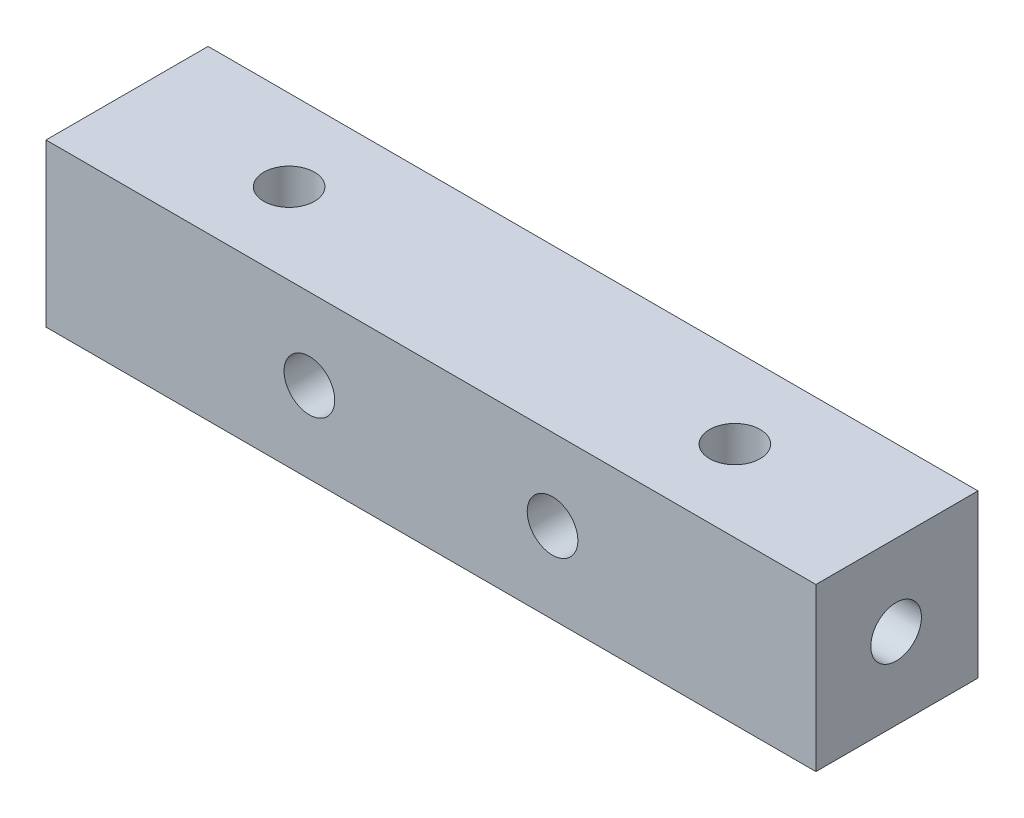
SolidWorks part; units mm, degrees
material "6061 合金"
ref_plane "前视基准面" through (0, 0, 0) normal (0, 0, 1) x (1, 0, 0)
ref_plane "上视基准面" through (0, 0, 0) normal (0, 1, 0) x (1, 0, 0)
ref_plane "右视基准面" through (0, 0, 0) normal (1, 0, 0) x (0, 0, -1)
sketch "草图1" plane through (0, 0, 0) normal (0, 0, 1) x (1, 0, 0)
  line L1 (19, -4) -> (-19, -4)
  line L2 (19, -4) -> (19, 4)
  line L3 (19, 4) -> (-19, 4)
  line L4 (-19, -4) -> (-19, 4)
  line L5 (19, -4) -> (-19, 4) construction
  line L6 (19, 4) -> (-19, -4) construction
  point P0 (0, 0)
  dimension "D1" = 38
  dimension "D2" = 8
extrude "凸台-拉伸1" add sketch "草图1" along normal blind 8
sketch "草图2" plane through (-19, 0, 0) normal (-1, 0, 0) x (0, 0, 1)
  line L0 (8, 4) -> (0, -4) construction
  line L1 (0, 4) -> (0, -4) construction
  line L2 (8, -4) -> (0, -4) construction
  line L3 (0, 4) -> (8, -4) construction
sketch "草图4" plane through (-19, 0, 0) normal (-1, 0, 0) x (0, 0, 1)
  point P0 (4.0412, 0)
hole_wizard "M3 螺纹孔的螺纹孔钻头1" positions "3D草图2" profile "草图5" hole size "M3" standard "DIN" end condition through all
sketch3d "3D草图2"
  point P0 (-19, 0, 4.0412)
sketch "草图5" plane through (-19, 0, 4.0412) normal (0, 1, 0) x (0, 0, 1)
  line L0 (0, 0) -> (0, 38)
  line L1 (0, 38) -> (1.25, 38)
  line L2 (1.25, 38) -> (1.25, 0)
  line L5 (1.25, 0) -> (0, 0)
  line L11 (0, -6.35) -> (0, 107.95) construction
  dimension "通孔孔直径" = 2.5
  dimension "通孔孔深度" = 38
sketch "草图6" plane through (0, 4, 0) normal (0, 1, 0) x (1, 0, 0)
  line L0 (-19, -8) -> (-19, 0) construction
  line L1 (19, -8) -> (19, 0) construction
  point P0 (-11, -4)
  point P1 (11, -4)
  dimension "D1" = 8
  dimension "D2" = 8
hole_wizard "M3 螺纹孔的螺纹孔钻头2" positions "3D草图3" profile "草图7" hole size "M3" standard "DIN" end condition through all
sketch3d "3D草图3"
  point P0 (-11, 4, 4)
sketch "草图7" plane through (-11, 4, 4) normal (1, 0, 0) x (0, 0, 1)
  line L0 (0, 0) -> (0, 8)
  line L1 (0, 8) -> (1.25, 8)
  line L2 (1.25, 8) -> (1.25, 0)
  line L5 (1.25, 0) -> (0, 0)
  line L11 (0, -6.35) -> (0, 107.95) construction
  dimension "通孔孔直径" = 2.5
  dimension "通孔孔深度" = 8
hole_wizard "M3 螺纹孔的螺纹孔钻头3" positions "3D草图4" profile "草图8" hole size "M3" standard "DIN" end condition through all
sketch3d "3D草图4"
  point P0 (11, 4, 4)
sketch "草图8" plane through (11, 4, 4) normal (1, 0, 0) x (0, 0, 1)
  line L0 (0, 0) -> (0, 8)
  line L1 (0, 8) -> (1.25, 8)
  line L2 (1.25, 8) -> (1.25, 0)
  line L5 (1.25, 0) -> (0, 0)
  line L11 (0, -6.35) -> (0, 107.95) construction
  dimension "通孔孔直径" = 2.5
  dimension "通孔孔深度" = 8
sketch "草图9" plane through (0, 0, 0) normal (0, 0, -1) x (-1, 0, 0)
  line L1 (19, 4) -> (19, -4) construction
  line L2 (-19, -4) -> (-19, 4) construction
  point P0 (6, 0)
  point P1 (-6, 0)
  dimension "D1" = 13
  dimension "D2" = 13
hole_wizard "M3 螺纹孔的螺纹孔钻头4" positions "3D草图5" profile "草图10" hole size "M3" standard "DIN" end condition through all
sketch3d "3D草图5"
  point P0 (-6, 0, 0)
sketch "草图10" plane through (-6, 0, 0) normal (1, 0, 0) x (0, 1, 0)
  line L0 (0, 0) -> (0, 8)
  line L1 (0, 8) -> (1.25, 8)
  line L2 (1.25, 8) -> (1.25, 0)
  line L5 (1.25, 0) -> (0, 0)
  line L11 (0, -6.35) -> (0, 107.95) construction
  dimension "通孔孔直径" = 2.5
  dimension "通孔孔深度" = 8
hole_wizard "M3 螺纹孔的螺纹孔钻头5" positions "3D草图6" profile "草图11" hole size "M3" standard "DIN" end condition through all
sketch3d "3D草图6"
  point P0 (6, 0, 0)
sketch "草图11" plane through (6, 0, 0) normal (1, 0, 0) x (0, 1, 0)
  line L0 (0, 0) -> (0, 8)
  line L1 (0, 8) -> (1.25, 8)
  line L2 (1.25, 8) -> (1.25, 0)
  line L5 (1.25, 0) -> (0, 0)
  line L11 (0, -6.35) -> (0, 107.95) construction
  dimension "通孔孔直径" = 2.5
  dimension "通孔孔深度" = 8
